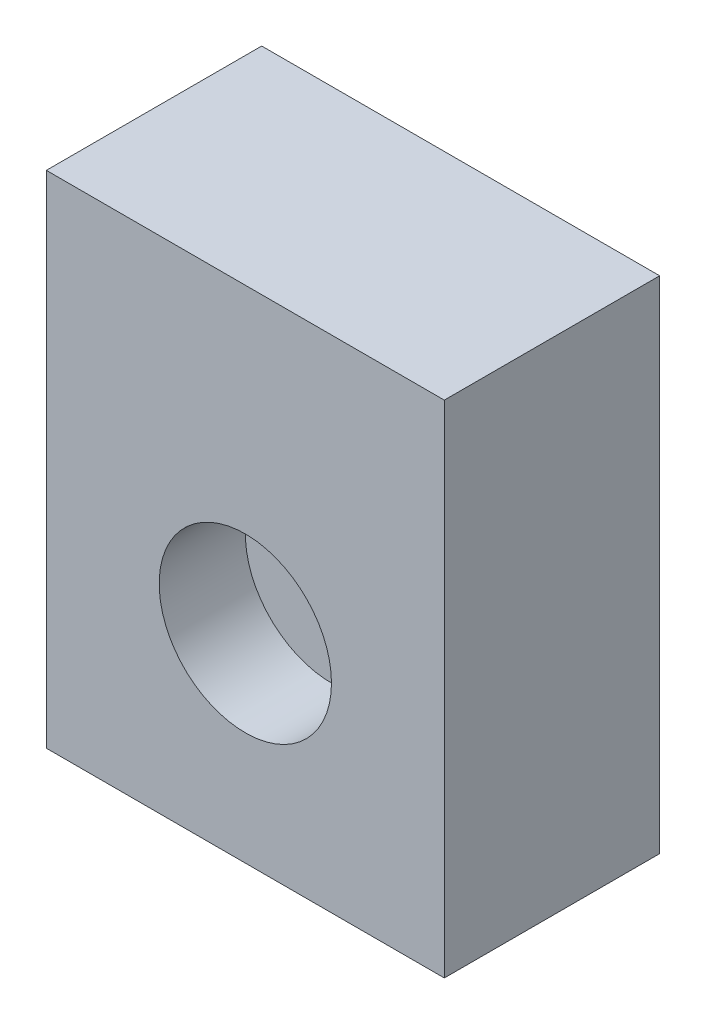
SolidWorks part; units mm, degrees
ref_plane "Front Plane" through (0, 0, 0) normal (0, 0, 1) x (1, 0, 0)
ref_plane "Top Plane" through (0, 0, 0) normal (0, 1, 0) x (1, 0, 0)
ref_plane "Right Plane" through (0, 0, 0) normal (1, 0, 0) x (0, 0, -1)
sketch "Sketch1" plane through (0, 0, 0) normal (0, 0, 1) x (1, 0, 0)
  line L1 (-4.62, 5.81) -> (4.62, 5.81)
  line L2 (-4.62, 5.81) -> (-4.62, -5.81)
  line L3 (-4.62, -5.81) -> (4.62, -5.81)
  line L4 (4.62, 5.81) -> (4.62, -5.81)
  line L5 (-4.62, 5.81) -> (4.62, -5.81) construction
  line L6 (-4.62, -5.81) -> (4.62, 5.81) construction
  point P0 (0, 0)
  dimension "D1" = 11.62
  dimension "D2" = 9.24
extrude "Boss-Extrude1" add sketch "Sketch1" along normal blind 5
sketch "Sketch2" plane through (0, 0, 5) normal (0, 0, 1) x (1, 0, 0)
  line L0 (-4.62, -5.81) -> (4.62, -5.81) construction
  line L1 (4.62, -5.81) -> (4.62, 5.81) construction
  circle A0 centre (0, -1.19) radius 2
  dimension "D1" = 4.62
  dimension "D2" = 4
  dimension "D3" = 4.62
extrude "Cut-Extrude1" cut sketch "Sketch2" against normal blind 2
